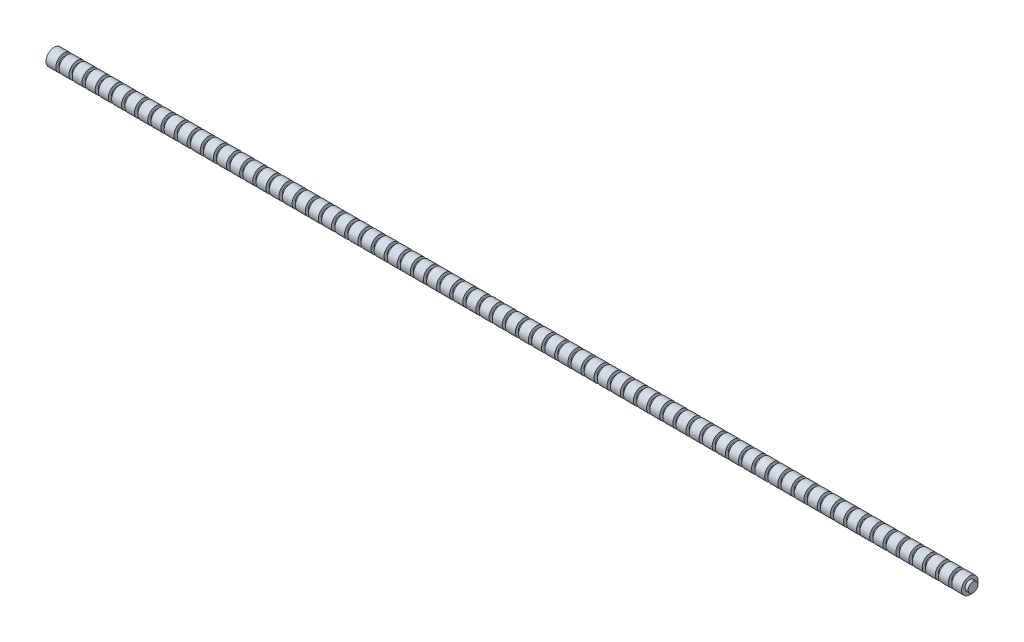
SolidWorks part; units mm, degrees
ref_plane "Front Plane" through (0, 0, 0) normal (0, 0, 1) x (1, 0, 0)
ref_plane "Top Plane" through (0, 0, 0) normal (0, 1, 0) x (1, 0, 0)
ref_plane "Right Plane" through (0, 0, 0) normal (1, 0, 0) x (0, 0, -1)
sketch "Sketch1" plane through (0, 0, 0) normal (1, 0, 0) x (0, 0, -1)
  circle A0 centre (0, 0) radius 3.175
  dimension "D1" = 6.35
extrude "Boss-Extrude1" add sketch "Sketch1" along normal blind 381
sketch "Sketch2" plane through (381, 0, 0) normal (1, 0, 0) x (0, 0, -1)
  circle A0 centre (0, 0) radius 1.905
  circle A1 centre (0, 0) radius 3.175
  circle A2 centre (0, 0) radius 3.175
  dimension "D2" = 1.27
  dimension "D1" = 0
extrude "Cut-Extrude1" cut sketch "Sketch2" against normal blind 1.27
pattern_linear "LPattern1" count 76 spacing 5.08 along (-1, 0, 0) of "Cut-Extrude1"
sketch "Sketch4" plane through (381, 0, 0) normal (1, 0, 0) x (0, 0, -1)
  circle A0 centre (0, 0) radius 3.175 construction
  circle A3 centre (0, 0) radius 3.175
extrude "Cut-Extrude2" cut sketch "Sketch4" against normal blind 25.4
